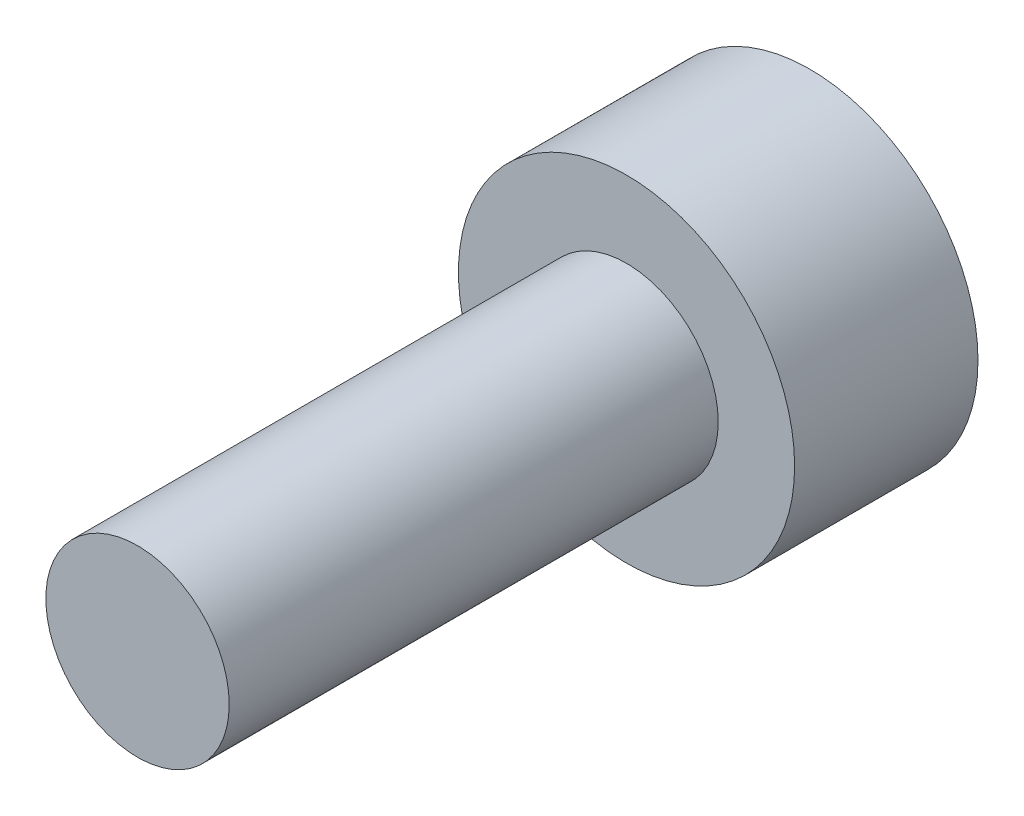
SolidWorks part; units mm, degrees
ref_plane "正面" through (0, 0, 0) normal (0, 0, 1) x (1, 0, 0)
ref_plane "平面" through (0, 0, 0) normal (0, 1, 0) x (1, 0, 0)
ref_plane "右側面" through (0, 0, 0) normal (1, 0, 0) x (0, 0, -1)
sketch "ｽｹｯﾁ1" plane through (0, 0, 0) normal (0, 0, 1) x (1, 0, 0)
  circle A0 centre (0, 0) radius 2.75
  dimension "D1" = 5.5
extrude "ﾎﾞｽ - 押し出し1" add sketch "ｽｹｯﾁ1" along normal blind 3
sketch "ｽｹｯﾁ2" plane through (0, 0, 3) normal (0, 0, 1) x (1, 0, 0)
  circle A0 centre (0, 0) radius 1.5
  dimension "D1" = 3
extrude "ﾎﾞｽ - 押し出し2" add sketch "ｽｹｯﾁ2" along normal blind 8
cosmetic thread "ねじ山1" parameters "D2"=3
sketch "ｽｹｯﾁ3" plane through (0, 0, 0) normal (0, 0, -1) x (-1, 0, 0)
  line L1 (1.6636, -0.3991) -> (1.1774, 1.2412)
  line L2 (1.1774, 1.2412) -> (-0.4862, 1.6403)
  line L3 (-0.4862, 1.6403) -> (-1.6636, 0.3991)
  line L4 (-1.6636, 0.3991) -> (-1.1774, -1.2412)
  line L5 (-1.1774, -1.2412) -> (0.4862, -1.6403)
  line L6 (0.4862, -1.6403) -> (1.6636, -0.3991)
  circle A0 centre (0, 0) radius 1.4816 construction
extrude "ｶｯﾄ - 押し出し1" cut sketch "ｽｹｯﾁ3" against normal blind 2
